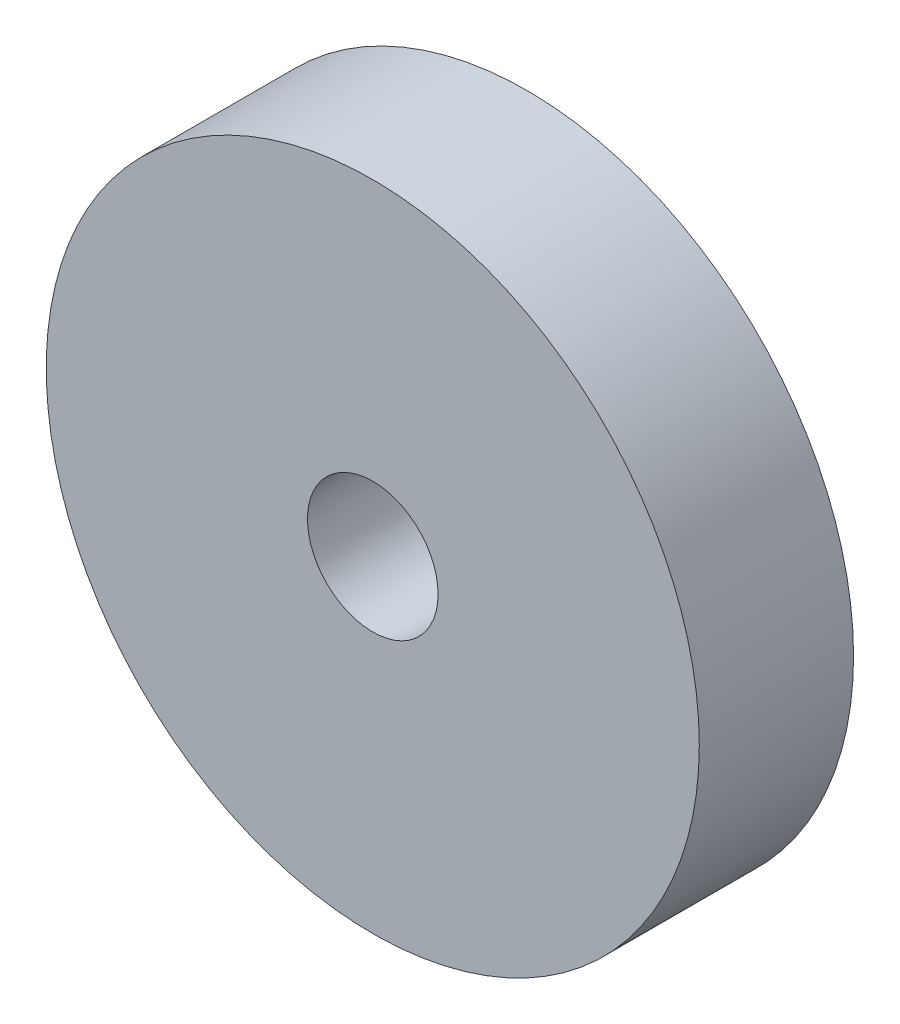
SolidWorks part; units mm, degrees
ref_plane "Alzado" through (0, 0, 0) normal (0, 0, 1) x (1, 0, 0)
ref_plane "Planta" through (0, 0, 0) normal (0, 1, 0) x (1, 0, 0)
ref_plane "Vista lateral" through (0, 0, 0) normal (1, 0, 0) x (0, 0, -1)
sketch "Croquis1" plane through (0, 0, 0) normal (0, 0, 1) x (1, 0, 0)
  circle A0 centre (0, 0) radius 63.5
  circle A1 centre (0, 0) radius 12.7
  dimension "D1" = 127
  dimension "D2" = 25.4
extrude "Saliente-Extruir1" add sketch "Croquis1" along normal blind 30
